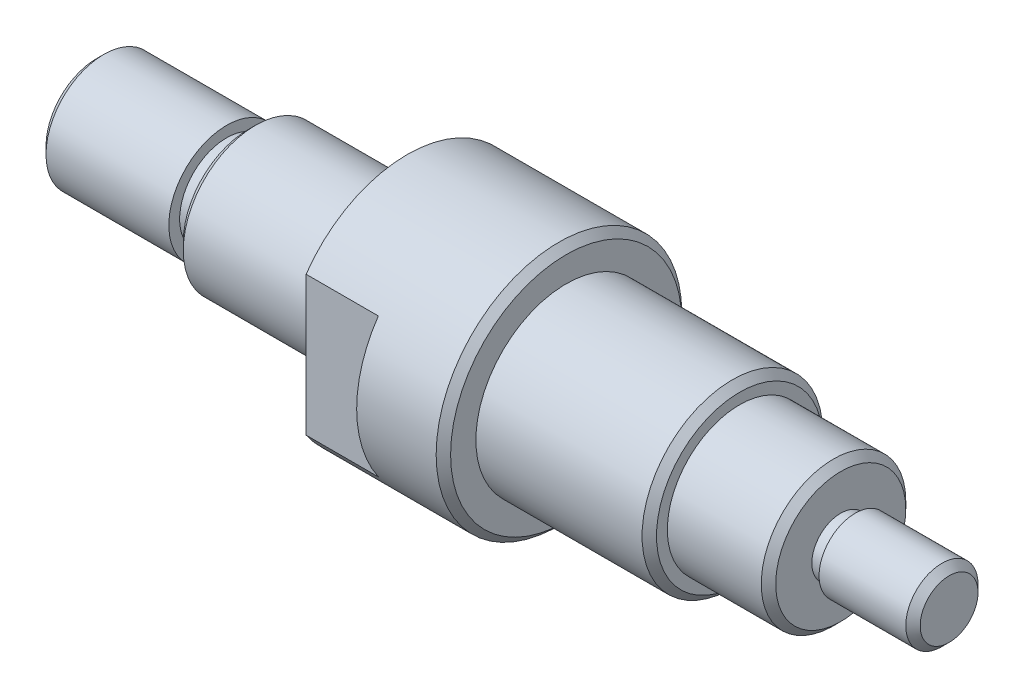
SolidWorks part; units mm, degrees
material "Alloy Steel"
ref_plane "Front Plane" through (0, 0, 0) normal (0, 0, 1) x (1, 0, 0)
ref_plane "Top Plane" through (0, 0, 0) normal (0, 1, 0) x (1, 0, 0)
ref_plane "Right Plane" through (0, 0, 0) normal (1, 0, 0) x (0, 0, -1)
sketch "Sketch1" plane through (0, 0, 0) normal (0, 0, 1) x (1, 0, 0)
  line L0 (0, 0) -> (-136.2702, 0) construction
  line L1 (0, 0) -> (0, 5)
  line L2 (0, 5) -> (-13, 5)
  line L3 (-13, 5) -> (-13, 4)
  line L4 (-13, 4) -> (-15, 4)
  line L5 (-15, 4) -> (-15, 10)
  line L6 (-15, 10) -> (-29, 10)
  line L7 (-29, 10) -> (-29, 12.5)
  line L8 (-29, 12.5) -> (-53, 12.5)
  line L9 (-53, 12.5) -> (-53, 17)
  line L10 (-53, 17) -> (-75, 17)
  line L11 (-75, 17) -> (-75, 10)
  line L12 (-75, 10) -> (-97, 10)
  line L13 (-97, 10) -> (-97, 6.5)
  line L14 (-97, 6.5) -> (-100, 6.5)
  line L15 (-100, 6.5) -> (-100, 8)
  line L16 (-100, 8) -> (-118, 8)
  line L17 (-118, 8) -> (-118, 0)
  line L18 (-118, 0) -> (0, 0)
  point P3 (-53, 14.75)
  point P21 (-14, 4)
  point P22 (-118, 4)
  dimension "D1" = 118
  dimension "D2" = 16
  dimension "D3" = 13
  dimension "D4" = 20
  dimension "D5" = 34
  dimension "D6" = 22
  dimension "D7" = 44
  dimension "D8" = 3
  dimension "D9" = 24
  dimension "D10" = 38
  dimension "D11" = 2
  dimension "D12" = 10
  dimension "D13" = 8
  dimension "D14" = 20
  dimension "D15" = 25
  dimension "D16" = 103
revolve "Revolve1" add sketch "Sketch1" angle 360 about L0
cosmetic thread "Cosmetic Thread3" parameters "D1"=13, "D2"=8.344
cosmetic thread "Cosmetic Thread4" parameters "D1"=18, "D2"=13.797
chamfer "Chamfer1" distance 1 6 edges at (-118, 0, -8) (-97, 0, -10) (-53, 0, -17) (-29, 0, -12.5) (-15, 0, -10) (0, 0, -5)
sketch "Sketch2" plane through (-75, 0, 0) normal (-1, 0, 0) x (0, 0, 1)
  line L0 (-14, 9.6437) -> (-14, -9.6437)
  line L1 (14, 9.6437) -> (14, -9.6437)
  circle A0 centre (0, 0) radius 17 construction
  circle A1 centre (0, 0) radius 17
  circle M5 centre (0, 0) radius 17
  dimension "D1" = 28
extrude "Cut-Extrude1" cut sketch "Sketch2" against normal blind 10 contours L0 M5 | L1 M5
